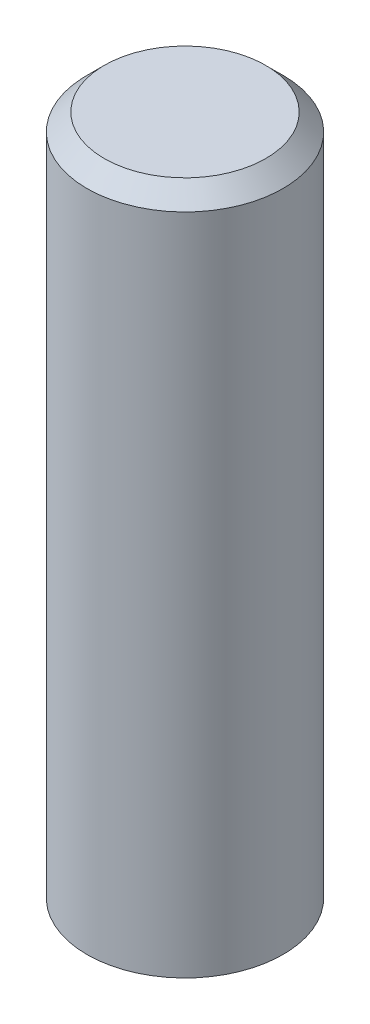
SolidWorks part; units mm, degrees
material "1.4305 (X8CrNiS18-9)"
ref_plane "Front Plane" through (0, 0, 0) normal (0, 0, 1) x (1, 0, 0)
ref_plane "Top Plane" through (0, 0, 0) normal (0, 1, 0) x (1, 0, 0)
ref_plane "Right Plane" through (0, 0, 0) normal (1, 0, 0) x (0, 0, -1)
ref_plane "Plane1" through (0, 0, 0) normal (0, 0, -1) x (-1, 0, 0)
sketch "Sketch1" plane through (0, 0, 0) normal (0, 0, -1) x (-1, 0, 0)
  line L0 (-1.7, 0) -> (0, 0)
  line L1 (0, 0) -> (0, 11.8)
  line L2 (0, 11.8) -> (-1.4, 11.8)
  line L3 (-1.4, 11.8) -> (-1.7, 11.5)
  line L4 (-1.7, 11.5) -> (-1.7, 0)
  line L5 (0, 0) -> (0, 11.8) construction
  dimension "D1" = 0.3
  dimension "D2" = 1.7
  dimension "D3" = 11.5
  dimension "D4" = 11.8
  dimension "D5" = 1.4
  dimension "D6" = 11.8
revolve "Revolve1" add sketch "Sketch1" angle 360 about L5
